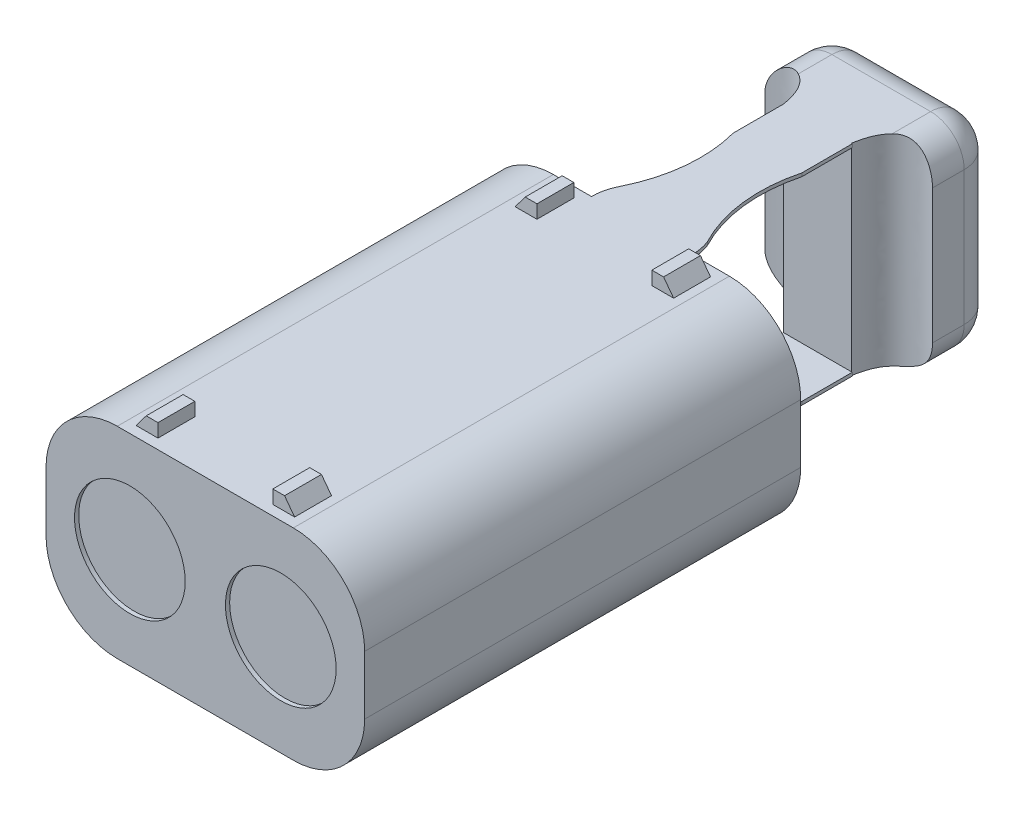
SolidWorks part; units mm, degrees
ref_plane "Front Plane" through (0, 0, 0) normal (0, 0, 1) x (1, 0, 0)
ref_plane "Top Plane" through (0, 0, 0) normal (0, 1, 0) x (1, 0, 0)
ref_plane "Right Plane" through (0, 0, 0) normal (1, 0, 0) x (0, 0, -1)
sketch "Sketch1" plane through (0, 0, 0) normal (0, 0, 1) x (1, 0, 0)
  line L0 (40.0799, 23.7006) -> (40.0799, -108.9023) construction
  line L1 (-54.9201, 23.7006) -> (135.0799, 23.7006)
  line L2 (-54.9201, 23.7006) -> (-54.9201, -96.2994)
  line L3 (-54.9201, -96.2994) -> (135.0799, -96.2994)
  line L4 (135.0799, 23.7006) -> (135.0799, -96.2994)
  line L5 (-54.9201, -36.2994) -> (176.8362, -36.2994) construction
  point P4 (-54.9201, -18.7994)
  point P9 (135.0799, -18.7994)
  point P10 (135.0799, -53.7994)
  point P11 (-54.9201, -53.7994)
  dimension "D1" = 190
  dimension "D2" = 120
  dimension "D3" = 17.5
extrude "Boss-Extrude1" add sketch "Sketch1" against normal blind 260 contours L1 L4 L3 L2
fillet "Fillet1" radius 42.5 4 edges at (135.0799, -96.2994, -130) (-54.9201, -96.2994, -130) (135.0799, 23.7006, -130) (-54.9201, 23.7006, -130)
sketch "Sketch2" plane through (0, 23.7006, 0) normal (0, 1, 0) x (1, 0, 0)
  line L0 (40.0799, 260) -> (40.0799, -7.3876) construction
  line L1 (-12.4201, 260) -> (92.5799, 260) construction
  line L2 (-12.4201, 130) -> (140.0707, 130) construction
  line L3 (-12.4201, 260) -> (-12.4201, 0) construction
  line L4 (-7.1701, 254) -> (-7.1701, 232)
  line L5 (74.3299, 254) -> (87.3299, 254)
  line L6 (74.3299, 254) -> (74.3299, 232)
  line L7 (74.3299, 232) -> (87.3299, 232)
  line L8 (87.3299, 254) -> (87.3299, 232)
  line L9 (5.8299, 232) -> (-7.1701, 232)
  line L10 (5.8299, 254) -> (5.8299, 232)
  line L11 (5.8299, 254) -> (-7.1701, 254)
  line L12 (5.8299, 6) -> (5.8299, 28)
  line L13 (5.8299, 28) -> (-7.1701, 28)
  line L14 (-7.1701, 6) -> (-7.1701, 28)
  line L15 (5.8299, 6) -> (-7.1701, 6)
  line L16 (87.3299, 6) -> (87.3299, 28)
  line L17 (74.3299, 28) -> (87.3299, 28)
  line L18 (74.3299, 6) -> (74.3299, 28)
  line L19 (74.3299, 6) -> (87.3299, 6)
  dimension "D1" = 22
  dimension "D2" = 28
  dimension "D3" = 13
  dimension "D4" = 68.5
extrude "Boss-Extrude2" add sketch "Sketch2" along normal blind 8
sketch "Sketch5" plane through (0, 0, -254) normal (0, 0, -1) x (-1, 0, 0)
  line L7 (-87.3299, 23.7006) -> (-81.3299, 31.7006)
  line L8 (-87.3299, 31.7006) -> (-74.3299, 31.7006) construction
  line L9 (-81.3299, 31.7006) -> (-87.3299, 31.7006)
  line L10 (-87.3299, 31.7006) -> (-87.3299, 23.7006) construction
  line L11 (-87.3299, 31.7006) -> (-87.3299, 23.7006)
  dimension "D1" = 7
extrude "Cut-Extrude5" cut sketch "Sketch5" against normal blind 32
sketch "Sketch7" plane through (0, 0, -254) normal (0, 0, -1) x (-1, 0, 0)
  line L0 (1.1701, 31.7006) -> (7.1701, 23.7006)
  line L1 (-5.8299, 31.7006) -> (7.1701, 31.7006) construction
  line L2 (7.1701, 23.7006) -> (7.1701, 31.7006)
  line L3 (7.1701, 31.7006) -> (1.1701, 31.7006)
  dimension "D1" = 7
extrude "Cut-Extrude6" cut sketch "Sketch7" against normal blind 32
ref_plane "Plane2" through (0, 0, -130) normal (0, 0, 1) x (1, 0, 0)
mirror "Mirror1" about plane through (0, 0, -130) normal (0, 0, 1) of "Cut-Extrude6", "Cut-Extrude5"
sketch "Sketch9" plane through (0, 23.7006, 0) normal (0, 1, 0) x (1, 0, 0)
  line L0 (74.3299, 254) -> (74.3299, 232) construction
  line L2 (10.3299, 260) -> (10.3299, 225)
  line L3 (10.3299, 225) -> (70.3299, 225)
  line L4 (70.3299, 260) -> (70.3299, 225)
  line L8 (19.8299, 364.9964) -> (60.8299, 364.9964)
  line L9 (19.8299, 364.9964) -> (19.8299, 334.9964)
  line L10 (20.5799, 225) -> (61.8299, 225)
  line L11 (60.8299, 364.9964) -> (60.8299, 334.9964)
  line L14 (40.0799, 230.3926) -> (40.0799, -43.259) construction
  arc A2 (13.944, 274.4375) -> (19.8299, 334.9964) centre (-64.4152, 312.6189) ccw
  arc A3 (68.2029, 271.2572) -> (60.8299, 334.9964) centre (146.575, 312.6189) cw
  arc A4 (70.3299, 260) -> (68.2029, 271.2572) centre (40.3299, 260.1612) ccw
  arc A5 (13.944, 274.4375) -> (10.3299, 260) centre (40.3299, 260.1612) ccw
  dimension "D1" = 60
  dimension "D2" = 35
  dimension "D4" = 4
  dimension "D5" = 41
  dimension "D6" = 9.5
  dimension "D7" = 140
extrude "Boss-Extrude3" add sketch "Sketch9" against normal blind 2
sketch "Sketch10" plane through (0, 0, -260) normal (0, 0, -1) x (-1, 0, 0)
  line L0 (-135.0799, -18.7994) -> (-135.0799, -53.7994) construction
  line L1 (12.4201, -96.2994) -> (-92.5799, -96.2994) construction
  circle A0 centre (-85.0799, -36.2994) radius 33
  dimension "D3" = 66
  dimension "D1" = 50
  dimension "D2" = 60
extrude "Cut-Extrude7" cut sketch "Sketch10" against normal mid plane 5
ref_plane "Plane3" through (40.0799, 0, 0) normal (1, 0, 0) x (0, 0, -1)
mirror "Mirror2" about plane through (40.0799, 0, 0) normal (1, 0, 0) of "Cut-Extrude7"
mirror "Mirror3" about plane through (0, 0, -130) normal (0, 0, 1) of "Cut-Extrude7", "Mirror2"
ref_plane "Plane4" through (0, -36.2994, 0) normal (0, 1, 0) x (1, 0, 0)
mirror "Mirror4" about plane through (0, -36.2994, 0) normal (0, 1, 0) of "Boss-Extrude3"
sketch "Sketch11" plane through (0, 0, -364.9964) normal (0, 0, -1) x (-1, 0, 0)
  line L0 (12.4201, -96.2994) -> (-10.3299, -96.2994) construction
  line L1 (-87.5773, 23.7006) -> (11.3337, 23.7006)
  line L2 (-87.5773, 23.7006) -> (-87.5773, -96.2994)
  line L3 (-87.5773, -96.2994) -> (11.3337, -96.2994)
  line L4 (11.3337, 23.7006) -> (11.3337, -96.2994)
  line L5 (-19.8299, 23.7006) -> (-60.8299, 23.7006) construction
extrude "Boss-Extrude4" add sketch "Sketch11" along normal blind 60
fillet "Fillet2" radius 20 8 edges at (-11.3337, 23.7006, -394.9964) (87.5773, 23.7006, -394.9964) (87.5773, -96.2994, -394.9964) (-11.3337, -96.2994, -394.9964) (38.1218, 23.7006, -424.9964) (87.5773, -36.2994, -424.9964) (-11.3337, -36.2994, -424.9964) (38.1218, -96.2994, -424.9964)
sketch "Sketch12" plane through (0, -96.2994, 0) normal (0, -1, 0) x (1, 0, 0)
  line L1 (-11.3337, -404.9964) -> (-11.3337, -364.9964) construction
  line L2 (-11.3337, -384.9964) -> (-11.3337, -364.9964)
  line L3 (-11.3337, -364.9964) -> (19.8299, -364.9964)
  line L4 (8.6663, -364.9964) -> (8.6663, -404.9964) construction
  spline S0 degree 2 poles (-11.3337, -384.9964) (15.2447, -393.7282) (19.8299, -364.9964) knots 0 0 0 1 1 1
extrude "Cut-Extrude8" cut sketch "Sketch12" against normal up to next
mirror "Mirror5" about plane through (40.0799, 0, 0) normal (1, 0, 0) of "Cut-Extrude8"
